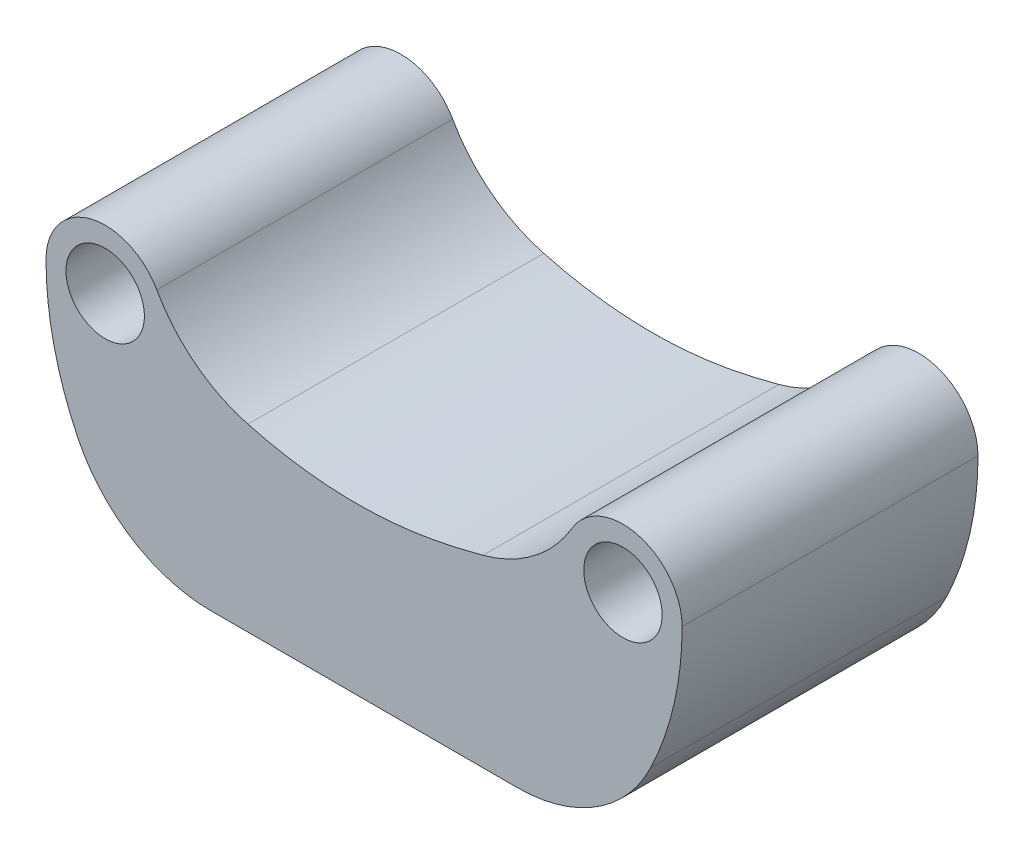
SolidWorks part; units mm, degrees
ref_plane "Piano frontale" through (0, 0, 0) normal (0, 0, 1) x (1, 0, 0)
ref_plane "Piano superiore" through (0, 0, 0) normal (0, 1, 0) x (1, 0, 0)
ref_plane "Piano destro" through (0, 0, 0) normal (1, 0, 0) x (0, 0, -1)
sketch "Schizzo1" plane through (0, 0, 0) normal (0, 0, 1) x (1, 0, 0)
  line L0 (-17.5, 0) -> (17.5, 0) construction
  line L1 (0, 0) -> (0, -3.8) construction
  line L2 (-15.4029, -15) -> (15.4029, -15)
  line L3 (-17.5, -15) -> (17.5, -15) construction
  circle A0 centre (-17.5, 0) radius 2.65
  circle A1 centre (17.5, 0) radius 2.65
  arc A2 (-14.0097, 1.954) -> (-21.5, 0) centre (-17.5, 0) ccw
  arc A3 (21.5, 0) -> (14.0523, 2.0281) centre (17.5, 0) ccw
  arc A4 (-21.5, 0) -> (-15.4029, -15) centre (0, 0) ccw
  arc A5 (8.0409, -2.5556) -> (14.0523, 2.0281) centre (5.433, 7.0984) ccw
  arc A6 (-7.8525, -2.8256) -> (-14.0097, 1.954) centre (-5.284, 6.8389) cw
  arc A7 (15.4029, -15) -> (21.5, 0) centre (0, 0) ccw
  spline S0 degree 3 poles (-7.8525, -2.8256) (-5.0631, -3.567) (0.1443, -4.133) (5.057, -3.3616) (8.0409, -2.5556) knots 0.170125 0.170125 0.170125 0.170125 0.505125 0.849603 0.849603 0.849603 0.849603
  point P4 (0, 0)
  dimension "D2" = 5.3
  dimension "D3" = 8
  dimension "D5" = 10
  dimension "D1" = 35
  dimension "D4" = 3.8
  dimension "D6" = 15
extrude "Estrusione-Estrusione1" add sketch "Schizzo1" along normal up to surface (20 mm away)
fillet "Raccordo1" radius 10 2 edges at (15.4029, -15, 10) (-15.4029, -15, 10)
